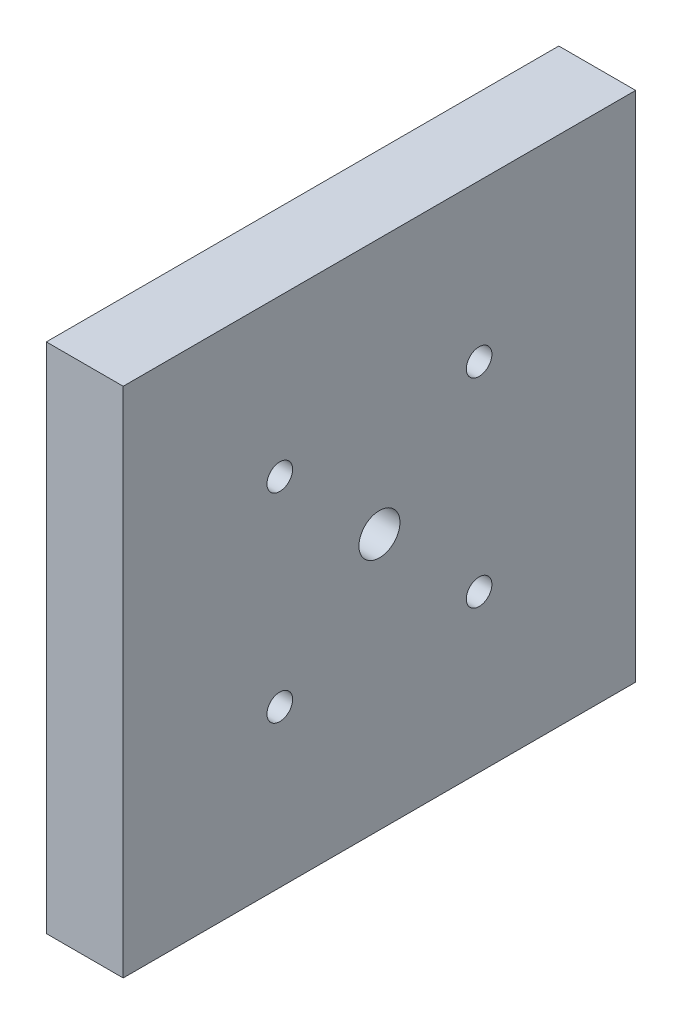
SolidWorks part; units mm, degrees
ref_plane "Ebene vorne" through (0, 0, 0) normal (0, 0, 1) x (1, 0, 0)
ref_plane "Ebene oben" through (0, 0, 0) normal (0, 1, 0) x (1, 0, 0)
ref_plane "Ebene rechts" through (0, 0, 0) normal (1, 0, 0) x (0, 0, -1)
sketch "Sketch2" plane through (0, 0, 0) normal (1, 0, 0) x (0, 0, -1)
  line L0 (-81.0651, 0) -> (92.8994, 0) construction
  line L1 (-50, 50) -> (50, 50)
  line L2 (-50, 50) -> (-50, -50)
  line L3 (-50, -50) -> (50, -50)
  line L4 (50, 50) -> (50, -50)
  line L5 (0, 88.4615) -> (0, -84.3195) construction
  circle A0 centre (0, 0) radius 4
  dimension "D1" = 100
  dimension "D2" = 100
extrude "Boss-Extrude1" add sketch "Sketch2" along normal blind 15
sketch "Sketch3" plane through (15, 0, 0) normal (1, 0, 0) x (0, 0, -1)
  line L2 (-76.29, 0) -> (76.29, 0) construction
  line L4 (-50, 50) -> (50, -50) construction
  line L5 (0, 50) -> (0, -50) construction
  line L6 (50, 50) -> (-50, 50) construction
  line L7 (-50, -50) -> (50, -50) construction
  circle A0 centre (0, 0) radius 76.29 construction
  circle A1 centre (-19.4454, 19.4454) radius 2.5
  circle A2 centre (19.4454, 19.4454) radius 2.5
  circle A3 centre (19.4454, -19.4454) radius 2.5
  circle A4 centre (-19.4454, -19.4454) radius 2.5
  point P17 (0, 0)
  point P27 (0, 0)
  dimension "D1" = 152.58
  dimension "D2" = 5
  dimension "D3" = 55
  dimension "D4" = 4
extrude "Cut-Extrude1" cut sketch "Sketch3" against normal blind 15
